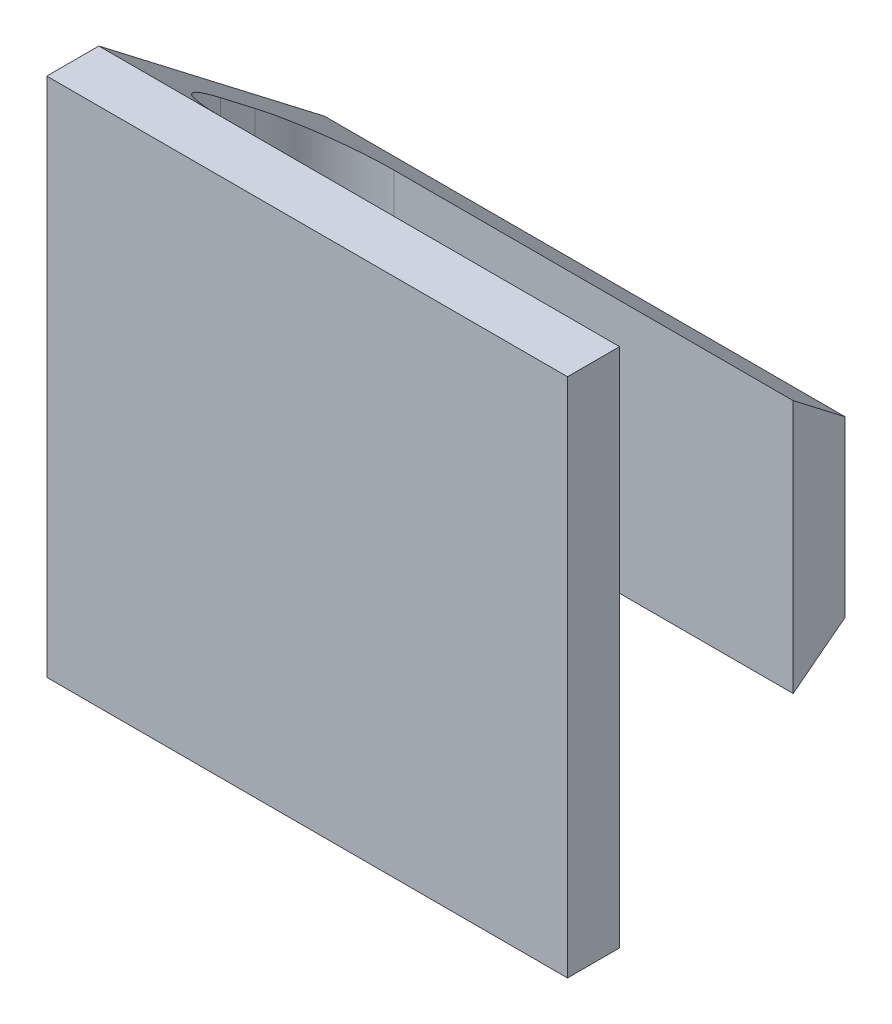
SolidWorks part; units mm, degrees
ref_plane "Front Plane" through (0, 0, 0) normal (0, 0, 1) x (1, 0, 0)
ref_plane "Top Plane" through (0, 0, 0) normal (0, 1, 0) x (1, 0, 0)
ref_plane "Right Plane" through (0, 0, 0) normal (1, 0, 0) x (0, 0, -1)
sketch "Sketch1" plane through (0, 0, 0) normal (0, 1, 0) x (1, 0, 0)
  line L1 (-6.7755, 3.314) -> (8.2245, 3.314)
  line L2 (-6.7755, 3.314) -> (-6.7755, 1.814)
  line L3 (-3.2755, 1.814) -> (8.2245, 1.814)
  line L4 (8.2245, 3.314) -> (8.2245, 1.814)
  line L6 (-6.7755, 1.814) -> (-6.7755, -3.186)
  line L8 (-5.2755, -0.186) -> (-5.2755, -1.186)
  line L9 (-3.2755, -3.186) -> (8.2245, -3.186)
  line L10 (-6.7755, -3.186) -> (-6.7755, -4.686)
  line L11 (-6.7755, -4.686) -> (8.2245, -4.686)
  line L12 (8.2245, -3.186) -> (8.2245, -4.686)
  arc A0 (-3.2755, -3.186) -> (-5.2755, -1.186) centre (-3.2755, -1.186) cw
  arc A1 (-3.2755, 1.814) -> (-5.2755, -0.186) centre (-3.2755, -0.186) ccw
  point P12 (-5.2755, -3.186)
  dimension "D6" = 2
  dimension "D1" = 15
  dimension "D2" = 1.5
  dimension "D3" = 5
  dimension "D4" = 1.5
  dimension "D5" = 1.5
extrude "Boss-Extrude1" add sketch "Sketch1" along normal blind 15
sketch "Sketch2" plane through (0, 0, 0) normal (1, 0, 0) x (0, 0, -1)
  line L0 (-3.186, 15) -> (3.314, 10)
  line L1 (3.314, 15) -> (3.314, 0) construction
  line L2 (3.314, 10) -> (3.314, 5)
  line L3 (3.314, 5) -> (-3.186, 0)
  line L4 (-3.186, 0) -> (5.5455, -1.9748)
  line L5 (5.5455, -1.9748) -> (16.3271, 9.0343)
  line L6 (16.3271, 9.0343) -> (5.0335, 17.7217)
  line L7 (5.0335, 17.7217) -> (-3.186, 15)
  line L8 (1.814, 15) -> (3.314, 15) construction
  line L9 (1.814, 0) -> (3.314, 0) construction
  dimension "D1" = 5
  dimension "D2" = 5
extrude "Cut-Extrude1" cut sketch "Sketch2" against normal blind 15 and the other way blind 15
